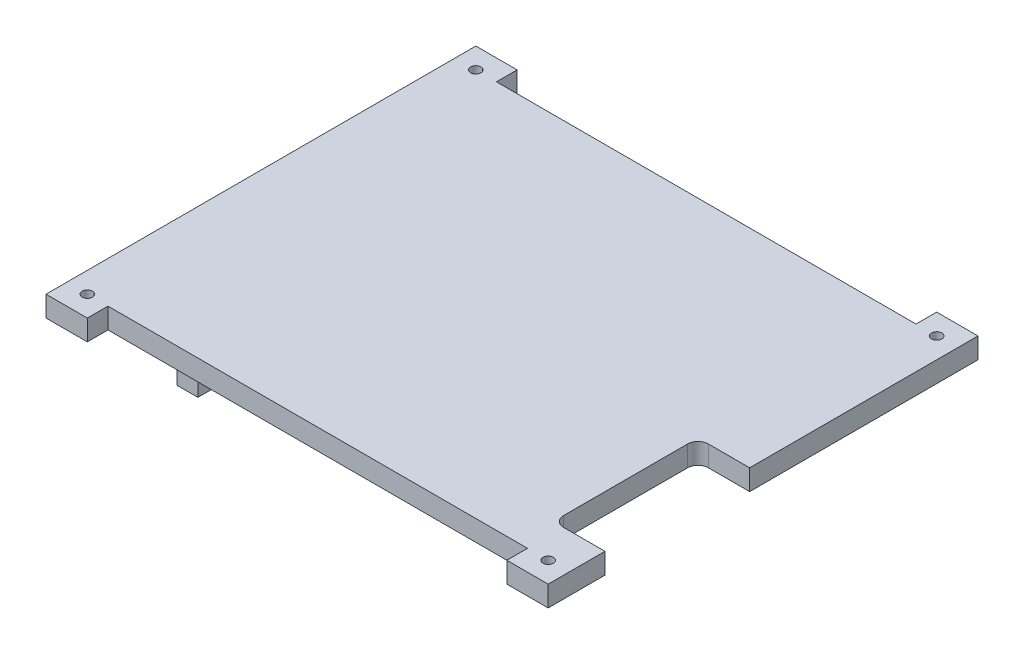
SolidWorks part; units mm, degrees
ref_plane "Front Plane" through (0, 0, 0) normal (0, 0, 1) x (1, 0, 0)
ref_plane "Top Plane" through (0, 0, 0) normal (0, 1, 0) x (1, 0, 0)
ref_plane "Right Plane" through (0, 0, 0) normal (1, 0, 0) x (0, 0, -1)
sketch "Sketch1" plane through (0, -1346.9084, 0) normal (0, 1, 0) x (1, 0, 0)
  line L0 (-1023.8323, 1967.9) -> (-1025.8323, 1967.9) construction
  line L1 (-1025.8323, 1967.9) -> (-1025.8323, 1966.4) construction
  line L2 (-1025.8323, 1966.4) -> (-1070.4323, 1966.4) construction
  line L3 (-1070.4323, 1966.4) -> (-1070.4323, 1974.9) construction
  line L4 (-1070.4323, 1974.9) -> (-1072.4323, 1974.9) construction
  line L5 (-1072.4323, 1974.9) -> (-1072.4323, 1962.4) construction
  line L6 (-1072.4323, 1962.4) -> (-1068.4323, 1962.4) construction
  line L7 (-1068.4323, 1962.4) -> (-1068.4323, 1964.4) construction
  line L8 (-1068.4323, 1964.4) -> (-1027.8323, 1964.4) construction
  line L9 (-1027.8323, 1964.4) -> (-1027.8323, 1962.4) construction
  line L10 (-1027.8323, 1962.4) -> (-1023.8323, 1962.4) construction
  line L11 (-1023.8323, 1962.4) -> (-1023.8323, 1967.9) construction
  line L12 (-1025.8323, 1981.9) -> (-1023.8323, 1981.9) construction
  line L13 (-1023.8323, 1981.9) -> (-1023.8323, 2004) construction
  line L14 (-1023.8323, 2004) -> (-1027.8323, 2004) construction
  line L15 (-1027.8323, 2004) -> (-1027.8323, 2002) construction
  line L16 (-1027.8323, 2002) -> (-1068.4323, 2002) construction
  line L17 (-1068.4323, 2002) -> (-1068.4323, 2004) construction
  line L18 (-1068.4323, 2004) -> (-1072.4323, 2004) construction
  line L19 (-1072.4323, 2004) -> (-1072.4323, 1991.5) construction
  line L20 (-1072.4323, 1991.5) -> (-1070.4323, 1991.5) construction
  line L21 (-1070.4323, 1991.5) -> (-1070.4323, 2000) construction
  line L22 (-1070.4323, 2000) -> (-1025.8323, 2000) construction
  line L23 (-1025.8323, 2000) -> (-1025.8323, 1981.9) construction
  line L24 (-1023.8323, 1967.9) -> (-1025.8323, 1967.9)
  line L25 (-1025.8323, 1967.9) -> (-1025.8323, 1966.4)
  line L26 (-1025.8323, 1966.4) -> (-1070.4323, 1966.4)
  line L27 (-1070.4323, 1966.4) -> (-1070.4323, 1974.9)
  line L28 (-1070.4323, 1974.9) -> (-1072.4323, 1974.9)
  line L29 (-1072.4323, 1974.9) -> (-1072.4323, 1962.4)
  line L30 (-1072.4323, 1962.4) -> (-1068.4323, 1962.4)
  line L31 (-1068.4323, 1962.4) -> (-1068.4323, 1964.4)
  line L32 (-1068.4323, 1964.4) -> (-1027.8323, 1964.4)
  line L33 (-1027.8323, 1964.4) -> (-1027.8323, 1962.4)
  line L34 (-1027.8323, 1962.4) -> (-1023.8323, 1962.4)
  line L35 (-1023.8323, 1962.4) -> (-1023.8323, 1967.9)
  line L36 (-1025.8323, 1981.9) -> (-1023.8323, 1981.9)
  line L37 (-1023.8323, 1981.9) -> (-1023.8323, 2004)
  line L38 (-1023.8323, 2004) -> (-1027.8323, 2004)
  line L39 (-1027.8323, 2004) -> (-1027.8323, 2002)
  line L40 (-1027.8323, 2002) -> (-1068.4323, 2002)
  line L41 (-1068.4323, 2002) -> (-1068.4323, 2004)
  line L42 (-1068.4323, 2004) -> (-1072.4323, 2004)
  line L43 (-1072.4323, 2004) -> (-1072.4323, 1991.5)
  line L44 (-1072.4323, 1991.5) -> (-1070.4323, 1991.5)
  line L45 (-1070.4323, 1991.5) -> (-1070.4323, 2000)
  line L46 (-1070.4323, 2000) -> (-1025.8323, 2000)
  line L47 (-1025.8323, 2000) -> (-1025.8323, 1981.9)
  line L48 (-1072.4323, 1991.5) -> (-1072.4323, 1974.9)
  line L49 (-1023.8323, 1981.9) -> (-1023.8323, 1967.9)
  circle A0 centre (-1070.4323, 1964.4) radius 0.5 construction
  circle A1 centre (-1025.8323, 1964.4) radius 0.5 construction
  circle A2 centre (-1025.8323, 2002) radius 0.5 construction
  circle A3 centre (-1070.4323, 2002) radius 0.5 construction
  circle A4 centre (-1070.4323, 1964.4) radius 0.5
  circle A5 centre (-1025.8323, 1964.4) radius 0.5
  circle A6 centre (-1025.8323, 2002) radius 0.5
  circle A7 centre (-1070.4323, 2002) radius 0.5
  circle M25 centre (-1025.8323, 2002) radius 0.5
  circle M26 centre (-1070.4323, 2002) radius 0.5
  line M27 (-1025.8323, 1981.9) -> (-1023.8323, 1981.9)
  line M28 (-1023.8323, 1981.9) -> (-1023.8323, 2004)
  line M29 (-1023.8323, 2004) -> (-1027.8323, 2004)
  line M30 (-1027.8323, 2004) -> (-1027.8323, 2002)
  line M31 (-1027.8323, 2002) -> (-1068.4323, 2002)
  line M32 (-1068.4323, 2002) -> (-1068.4323, 2004)
  line M33 (-1068.4323, 2004) -> (-1072.4323, 2004)
  line M34 (-1072.4323, 2004) -> (-1072.4323, 1991.5)
  line M35 (-1072.4323, 1991.5) -> (-1070.4323, 1991.5)
  line M36 (-1070.4323, 1991.5) -> (-1070.4323, 2000)
  line M37 (-1070.4323, 2000) -> (-1025.8323, 2000)
  line M38 (-1025.8323, 2000) -> (-1025.8323, 1981.9)
extrude "Boss-Extrude1" add sketch "Sketch1" along normal blind 2 contours M38 M27 M28 M29 M30 M31 M32 M33 M34 M35 M36 M37 M26 M25 | L49 L48 L28 L27 L26 L25 L24 M27 M38 M37 M36 M35 | L34 L35 L24 L25 L26 L27 L28 L29 L30 L31 L32 L33 A5 A4
ref_plane "Plane1" through (-1068.4323, -1344.9084, -1964.4) normal (1, 0, 0) x (0, 0, -1)
sketch "Sketch3" plane through (0, -1344.9084, 0) normal (0, 1, 0) x (1, 0, 0)
  line L0 (-1025.8323, 1967.9) -> (-1023.8323, 1967.9) construction
  line L1 (-1023.8323, 1981.9) -> (-1025.8323, 1981.9) construction
  line L2 (-1025.8323, 1967.9) -> (-1023.8323, 1967.9)
  line L3 (-1023.8323, 1981.9) -> (-1025.8323, 1981.9)
  line L5 (-1023.8323, 1967.9) -> (-1028.8323, 1967.9)
  line L6 (-1023.8323, 1967.9) -> (-1023.8323, 1981.9)
  line L7 (-1023.8323, 1981.9) -> (-1028.8323, 1981.9)
  line L8 (-1028.8323, 1967.9) -> (-1028.8323, 1981.9)
  line M10 (-1023.8323, 1962.4) -> (-1023.8323, 2004)
  dimension "D1" = 5
extrude "Cut-Extrude1" cut sketch "Sketch3" against normal blind 2 contours L8 L5 L2 L3 L7 M10
fillet "Fillet1" radius 1 2 edges at (-1028.8323, -1345.9084, -1981.9) (-1028.8323, -1345.9084, -1967.9)
sketch "Sketch4" plane through (0, -1346.9084, 0) normal (0, -1, 0) x (1, 0, 0)
  line L0 (-1072.4323, -2004) -> (-1072.4323, -1962.4) construction
  line L1 (-1072.4323, -1991.3) -> (-1070.4323, -1991.3)
  line L2 (-1072.4323, -1991.3) -> (-1072.4323, -1975.1)
  line L3 (-1072.4323, -1975.1) -> (-1070.4323, -1975.1)
  line L4 (-1070.4323, -1991.3) -> (-1070.4323, -1975.1)
  dimension "D1" = 0.2
  dimension "D2" = 0.2
  dimension "D3" = 2
extrude "Boss-Extrude2" add sketch "Sketch4" along normal offset from surface (12 mm away) 8
